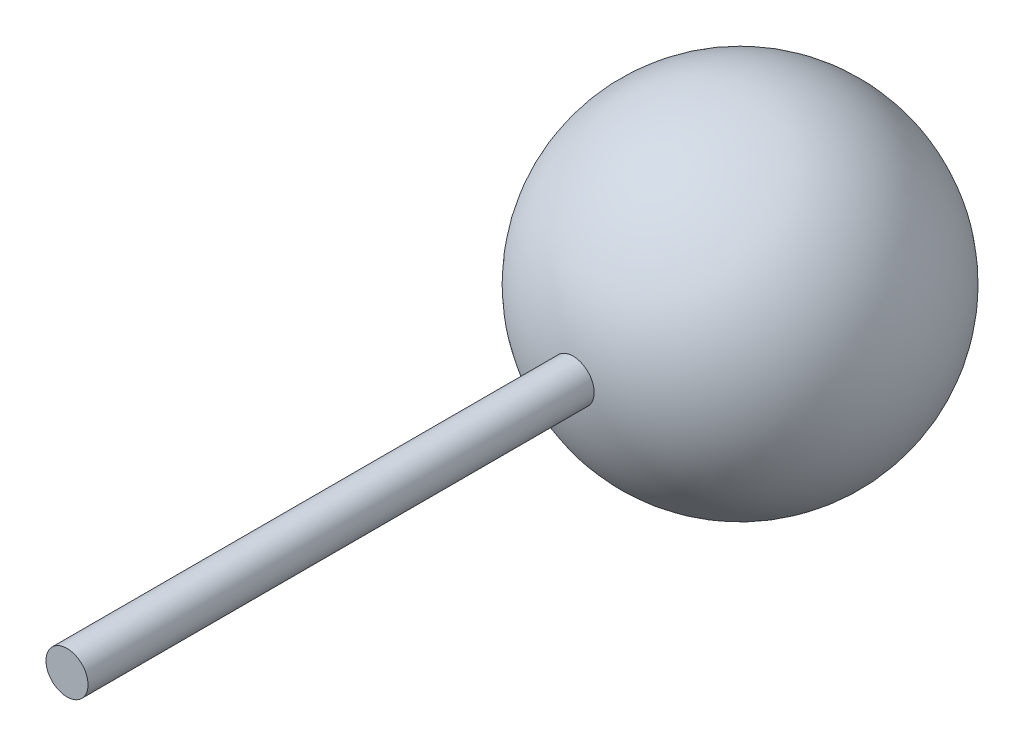
SolidWorks part; units mm, degrees
ref_plane "Front Plane" through (0, 0, 0) normal (0, 0, 1) x (1, 0, 0)
ref_plane "Top Plane" through (0, 0, 0) normal (0, 1, 0) x (1, 0, 0)
ref_plane "Right Plane" through (0, 0, 0) normal (1, 0, 0) x (0, 0, -1)
sketch "Sketch1" plane through (0, 0, 0) normal (0, 1, 0) x (1, 0, 0)
  line L0 (0, 6.35) -> (0, -6.35)
  arc A0 (0, -6.35) -> (0, 6.35) centre (0, 0) ccw
  dimension "D1" = 12.7
revolve "Revolve1" add sketch "Sketch1" angle 360 about L0
sketch "Sketch2" plane through (0, 0, 0) normal (0, 0, 1) x (1, 0, 0)
  circle A0 centre (0, 0) radius 0.7938
  dimension "D1" = 1.5875
extrude "Boss-Extrude1" add sketch "Sketch2" along normal blind 25.4
